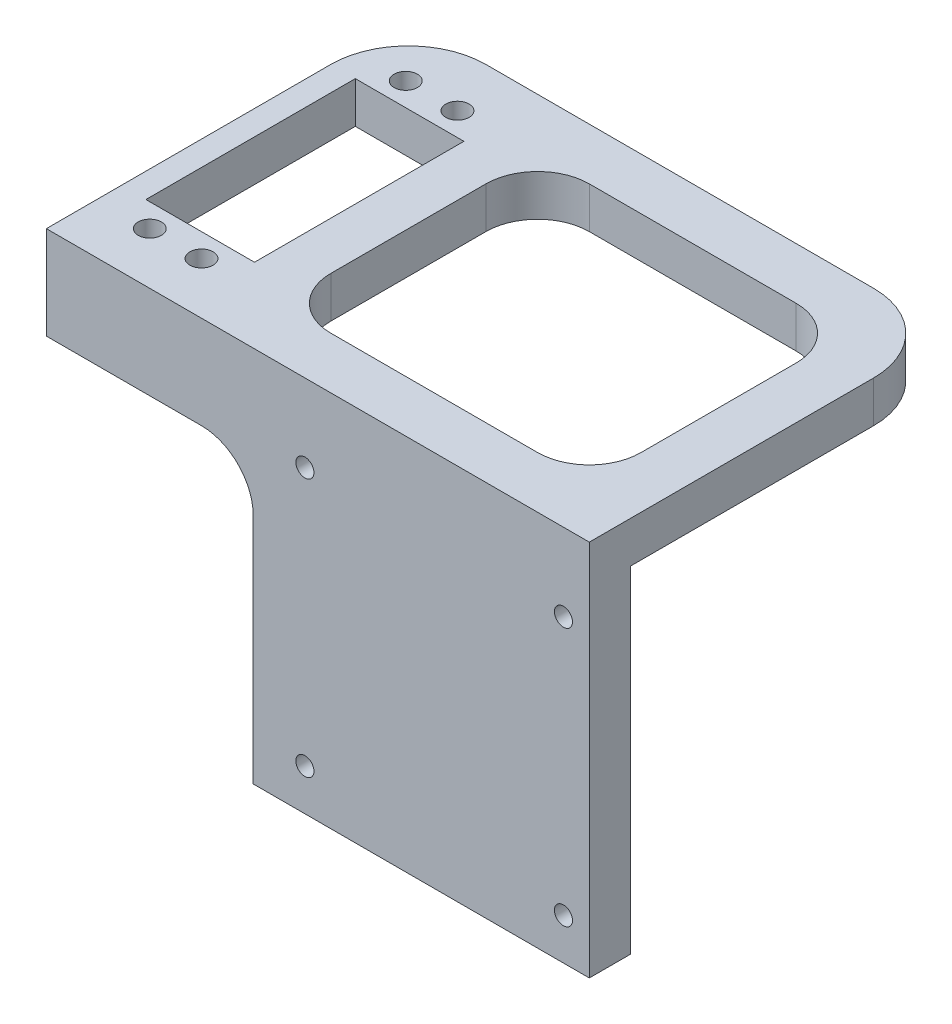
SolidWorks part; units mm, degrees
ref_plane "Front Plane" through (0, 0, 0) normal (0, 0, 1) x (1, 0, 0)
ref_plane "Top Plane" through (0, 0, 0) normal (0, 1, 0) x (1, 0, 0)
ref_plane "Right Plane" through (0, 0, 0) normal (1, 0, 0) x (0, 0, -1)
sketch "Sketch2" plane through (0, 0, 0) normal (0, 1, 0) x (1, 0, 0)
  line L1 (-15, 37.5) -> (90, 37.5)
  line L2 (-15, 37.5) -> (-15, -32.5)
  line L3 (-15, -32.5) -> (90, -32.5)
  line L4 (90, 37.5) -> (90, -32.5)
  dimension "D1" = 105
  dimension "D2" = 70
  dimension "D3" = 90
  dimension "D4" = 37.5
extrude "Boss-Extrude1" add sketch "Sketch2" along normal blind 8
sketch "Sketch4" plane through (0, 0, 0) normal (0, -1, 0) x (-1, 0, 0)
  line L0 (-90, -32.5) -> (-90, 37.5) construction
  line L1 (15, -32.5) -> (-90, -32.5)
  line L2 (15, -32.5) -> (15, -24.5)
  line L3 (15, -24.5) -> (-90, -24.5)
  line L4 (-90, -32.5) -> (-90, -24.5)
  dimension "D1" = 8
extrude "Boss-Extrude2" add sketch "Sketch4" along normal blind 65
sketch "Sketch6" plane through (0, 0, 24.5) normal (0, 0, -1) x (-1, 0, 0)
  line L0 (15, 0) -> (-90, 0) construction
  line L1 (-90, -65) -> (-90, 0) construction
  circle A0 centre (-85, -7) radius 1.75
  circle A1 centre (-35, -7) radius 1.75
  circle A2 centre (-85, -57) radius 1.75
  circle A3 centre (-35, -57) radius 1.75
  dimension "D1" = 3.5
  dimension "D2" = 3.5
  dimension "D3" = 3.5
  dimension "D4" = 3.5
  dimension "D5" = 7
  dimension "D6" = 7
  dimension "D7" = 50
  dimension "D8" = 50
  dimension "D9" = 50
  dimension "D10" = 5
  dimension "D11" = 5
extrude "Cut-Extrude1" cut sketch "Sketch6" against normal blind 10
sketch "Sketch7" plane through (0, 0, 24.5) normal (0, 0, -1) x (-1, 0, 0)
  circle A0 centre (-85, -7) radius 3.5
  circle A1 centre (-35, -7) radius 3.5
  circle A2 centre (-35, -57) radius 3.5
  circle A3 centre (-85, -57) radius 3.5
  dimension "D1" = 7
  dimension "D2" = 7
  dimension "D3" = 7
  dimension "D4" = 7
extrude "Cut-Extrude2" cut sketch "Sketch7" against normal blind 3
sketch "Sketch9" plane through (0, 8, 0) normal (0, 1, 0) x (1, 0, 0)
  line L0 (-15, -32.5) -> (90, -32.5) construction
  line L1 (-10.25, 22.5) -> (10.75, 22.5)
  line L2 (-10.25, 22.5) -> (-10.25, -18)
  line L3 (-10.25, -18) -> (10.75, -18)
  line L4 (10.75, 22.5) -> (10.75, -18)
  dimension "D1" = 21
  dimension "D2" = 40.5
  dimension "D3" = 10.25
  dimension "D4" = 55
extrude "Cut-Extrude3" cut sketch "Sketch9" against normal blind 10
sketch "Sketch10" plane through (0, 8, 0) normal (0, 1, 0) x (1, 0, 0)
  line L0 (10.75, 22.5) -> (-10.25, 22.5) construction
  circle A0 centre (-5, 27) radius 2.25
  circle A1 centre (5, 27) radius 2.25
  circle A2 centre (-5, -22.5) radius 2.25
  circle A3 centre (5, -22.5) radius 2.25
  dimension "D1" = 4.5
  dimension "D2" = 4.5
  dimension "D3" = 4.5
  dimension "D4" = 4.5
  dimension "D5" = 5
  dimension "D6" = 5
  dimension "D7" = 5
  dimension "D8" = 5
  dimension "D9" = 49.5
  dimension "D10" = 49.5
  dimension "D11" = 4.5
  dimension "D12" = 4.5
extrude "Cut-Extrude4" cut sketch "Sketch10" against normal blind 10
fillet "Fillet1" radius 15 1 edges at (90, 4, -37.5)
fillet "Fillet2" radius 15 1 edges at (-15, 4, -37.5)
sketch "Sketch12" plane through (0, 8, 0) normal (0, 1, 0) x (1, 0, 0)
  line L0 (75, 37.5) -> (0, 37.5) construction
  line L1 (20, 27.5) -> (80, 27.5)
  line L2 (20, 27.5) -> (20, -22.5)
  line L3 (20, -22.5) -> (80, -22.5)
  line L4 (80, 27.5) -> (80, -22.5)
  line L5 (90, -32.5) -> (90, 22.5) construction
  dimension "D1" = 60
  dimension "D2" = 50
  dimension "D3" = 10
  dimension "D4" = 10
extrude "Cut-Extrude5" cut sketch "Sketch12" against normal blind 10
fillet "Fillet3" radius 10 1 edges at (20, 4, 22.5)
fillet "Fillet4" radius 10 1 edges at (80, 4, 22.5)
fillet "Fillet5" radius 10 1 edges at (80, 4, -27.5)
fillet "Fillet6" radius 10 1 edges at (20, 4, -27.5)
sketch "Sketch13" plane through (0, 0, 24.5) normal (0, 0, -1) x (-1, 0, 0)
  line L0 (15, 0) -> (6.0308, 0) construction
  line L1 (15, -65) -> (-25, -65)
  line L2 (15, -65) -> (15, -10)
  line L3 (15, -10) -> (-25, -10)
  line L4 (-25, -65) -> (-25, -10)
  circle A0 centre (-35, -7) radius 1.75 construction
  dimension "D1" = 10
  dimension "D2" = 10
extrude "Cut-Extrude6" cut sketch "Sketch13" against normal blind 10
fillet "Fillet7" radius 10 1 edges at (25, -10, 28.5)
